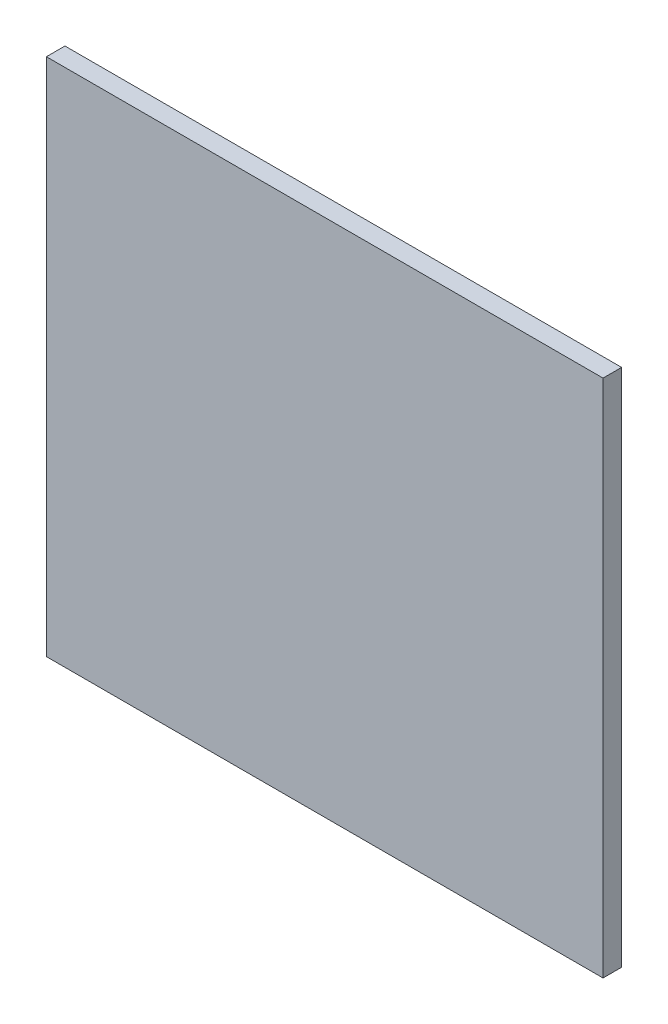
SolidWorks part; units mm, degrees
ref_plane "Ebene vorne" through (0, 0, 0) normal (0, 0, 1) x (1, 0, 0)
ref_plane "Ebene oben" through (0, 0, 0) normal (0, 1, 0) x (1, 0, 0)
ref_plane "Ebene rechts" through (0, 0, 0) normal (1, 0, 0) x (0, 0, -1)
sketch "Sketch1" plane through (0, 0, 0) normal (0, 0, 1) x (1, 0, 0)
  line L1 (0, 0) -> (30, 0)
  line L2 (0, 0) -> (0, 28)
  line L3 (0, 28) -> (30, 28)
  line L4 (30, 0) -> (30, 28)
  dimension "D1" = 28
  dimension "D2" = 30
extrude "Boss-Extrude1" add sketch "Sketch1" along normal blind 1
